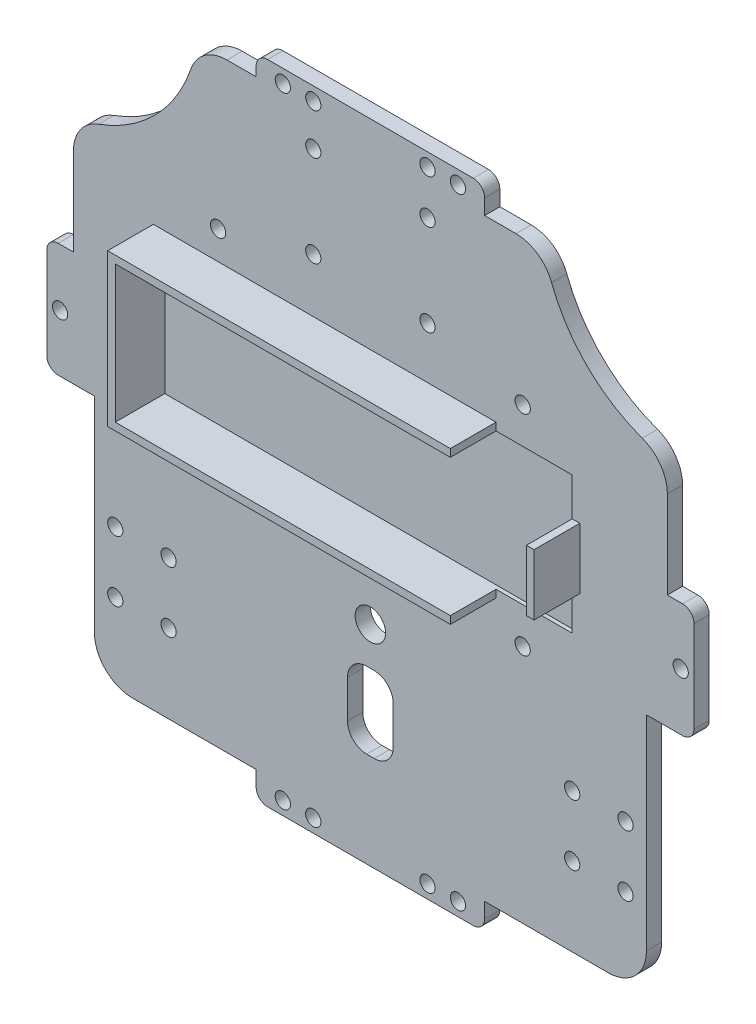
SolidWorks part; units mm, degrees
ref_plane "Front Plane" through (0, 0, 0) normal (0, 0, 1) x (1, 0, 0)
ref_plane "Top Plane" through (0, 0, 0) normal (0, 1, 0) x (1, 0, 0)
ref_plane "Right Plane" through (0, 0, 0) normal (1, 0, 0) x (0, 0, -1)
sketch "Sketch1" plane through (0, 0, 0) normal (0, 0, 1) x (1, 0, 0)
  line L0 (82, 15) -> (78, 15)
  line L7 (78, 15) -> (78, 37.9787)
  line L10 (85, -12) -> (85, 12)
  line L11 (30, -82.6865) -> (30, -78.6865)
  line L12 (-82, 15) -> (-78, 15)
  line L13 (-82, -15) -> (-72.5, -15)
  line L14 (-85, -12) -> (-85, 12)
  line L16 (-78, 15) -> (-78, 37.9787)
  line L17 (72.5, -15) -> (82, -15)
  line L18 (30, 81.3135) -> (30, 77.3135)
  line L19 (30, 77.3135) -> (38.2326, 77.3135)
  line L20 (-30, 81.3135) -> (-30, 78.8612)
  line L21 (-30, 78.8612) -> (-37.6762, 78.8612)
  line L22 (-27, 84.3135) -> (27, 84.3135)
  line L23 (30, -78.6865) -> (62.5, -78.6865)
  line L24 (-30, -82.6865) -> (-30, -78.6865)
  line L25 (-30, -78.6865) -> (-62.5, -78.6865)
  line L26 (-27, -85.6865) -> (27, -85.6865)
  line L27 (72.5, -15) -> (72.5, -68.6865)
  line L28 (-72.5, -68.6865) -> (-72.5, -15)
  arc A0 (47.5861, 70.8508) -> (71.4, 47.383) centre (85, 85) ccw
  arc A1 (-71.4, 47.383) -> (-47.141, 72.0889) centre (-85, 85) ccw
  arc A2 (-27, 84.3135) -> (-30, 81.3135) centre (-27, 81.3135) ccw
  arc A3 (85, 12) -> (82, 15) centre (82, 12) ccw
  arc A4 (30, 81.3135) -> (27, 84.3135) centre (27, 81.3135) ccw
  arc A5 (82, -15) -> (85, -12) centre (82, -12) ccw
  arc A6 (-82, -15) -> (-85, -12) centre (-82, -12) cw
  arc A7 (-85, 12) -> (-82, 15) centre (-82, 12) cw
  arc A8 (-27, -85.6865) -> (-30, -82.6865) centre (-27, -82.6865) cw
  arc A9 (27, -85.6865) -> (30, -82.6865) centre (27, -82.6865) ccw
  arc A10 (-37.6762, 78.8612) -> (-47.141, 72.0889) centre (-37.6762, 68.8612) ccw
  arc A11 (-78, 37.9787) -> (-71.4, 47.383) centre (-68, 37.9787) cw
  arc A12 (47.5861, 70.8508) -> (38.2326, 77.3135) centre (38.2326, 67.3135) ccw
  arc A13 (78, 37.9787) -> (71.4, 47.383) centre (68, 37.9787) ccw
  arc A14 (72.5, -68.6865) -> (62.5, -78.6865) centre (62.5, -68.6865) cw
  arc A15 (-72.5, -68.6865) -> (-62.5, -78.6865) centre (-62.5, -68.6865) ccw
  point P0 (0, 0)
  point P23 (85, 15)
  point P33 (30, 84.3135)
  point P36 (85, -15)
  point P47 (30, -85.6865)
  point P56 (78, 45.6173)
  dimension "D4" = 40
  dimension "D5" = 40
  dimension "D6" = 145
  dimension "D31" = 3
  dimension "D29" = 3
  dimension "D32" = 3
  dimension "D33" = 3
  dimension "D34" = 3
  dimension "D35" = 3
  dimension "D36" = 3
  dimension "D37" = 10
  dimension "D38" = 10
  dimension "D39" = 10
  dimension "D40" = 10
  dimension "D41" = 10
  dimension "D42" = 10
  dimension "D7" = 55
  dimension "D8" = 55
  dimension "D9" = 30
  dimension "D10" = 12.5
  dimension "D11" = 7
  dimension "D12" = 55
  dimension "D13" = 7
  dimension "D14" = 55
  dimension "D15" = 7
  dimension "D16" = 85
  dimension "D17" = 170
  dimension "D18" = 7
  dimension "D19" = 170.6865
  dimension "D20" = 85.6865
  dimension "D21" = 7
  dimension "D22" = 170
  dimension "D23" = 30.6173
  dimension "D24" = 70.6865
  dimension "D25" = 5.4523
  dimension "D26" = 70.6865
  dimension "D27" = 30
  dimension "D28" = 170.6865
  dimension "D30" = 170
extrude "Boss-Extrude1" add sketch "Sketch1" along normal blind 4
sketch "Sketch2" plane through (0, 0, 4) normal (0, 0, 1) x (1, 0, 0)
  line L0 (82, 15) -> (78, 15) construction
  line L1 (85, -12) -> (85, 12) construction
  line L2 (-85, 12) -> (-85, -12) construction
  line L3 (-78, 15) -> (-82, 15) construction
  line L4 (27, 84.3135) -> (-27, 84.3135) construction
  line L5 (30, 77.3135) -> (30, 81.3135) construction
  line L6 (-30, 81.3135) -> (-30, 78.8612) construction
  line L7 (-27, -85.6865) -> (27, -85.6865) construction
  line L8 (30, -82.6865) -> (30, -78.6865) construction
  line L9 (-30, -78.6865) -> (-30, -82.6865) construction
  line L19 (-1, -40.6865) -> (1, -40.6865)
  line L20 (-6, -45.6865) -> (-6, -55.6865)
  line L21 (-1, -60.6865) -> (1, -60.6865)
  line L22 (6, -45.6865) -> (6, -55.6865)
  line L23 (72.5, -15) -> (82, -15) construction
  line L26 (-62.5, -78.6865) -> (-30, -78.6865) construction
  line L27 (-72.5, -15) -> (-72.5, -68.6865) construction
  circle A0 centre (81.5, 0) radius 2
  circle A1 centre (-81.5, 0) radius 2
  circle A2 centre (15, 80.8135) radius 2
  circle A3 centre (23, 80.8135) radius 2
  circle A4 centre (-23, 80.8135) radius 2
  circle A5 centre (-15, 80.8135) radius 2
  circle A6 centre (-23, -82.1865) radius 2
  circle A7 centre (-15, -82.1865) radius 2
  circle A8 centre (15, -82.1865) radius 2
  circle A9 centre (23, -82.1865) radius 2
  circle A11 centre (67, -42) radius 2
  circle A12 centre (67, -58) radius 2
  arc A19 (6, -45.6865) -> (1, -40.6865) centre (1, -45.6865) ccw
  arc A20 (-6, -45.6865) -> (-1, -40.6865) centre (-1, -45.6865) cw
  arc A21 (1, -60.6865) -> (6, -55.6865) centre (1, -55.6865) ccw
  arc A22 (-1, -60.6865) -> (-6, -55.6865) centre (-1, -55.6865) cw
  circle A25 centre (-40, -15.6865) radius 2
  circle A26 centre (40, -15.6865) radius 2
  circle A27 centre (40, 39.3135) radius 2
  circle A28 centre (-40, 39.3135) radius 2
  circle A29 centre (0, -30.6865) radius 4
  circle A30 centre (-15, 70.0079) radius 2
  circle A31 centre (15, 69.3135) radius 2
  circle A32 centre (-15, 46.0079) radius 2
  circle A33 centre (15, 45.3135) radius 2
  circle A34 centre (53, -58) radius 2
  circle A35 centre (53, -42) radius 2
  circle A36 centre (-53, -58) radius 2
  circle A37 centre (-67, -58) radius 2
  circle A38 centre (-67, -42) radius 2
  circle A39 centre (-53, -42) radius 2
  point P59 (6, -40.6865)
  point P65 (-6, -40.6865)
  dimension "D1" = 4
  dimension "D4" = 4
  dimension "D7" = 4
  dimension "D8" = 4
  dimension "D13" = 4
  dimension "D14" = 4
  dimension "D17" = 3.5
  dimension "D21" = 4
  dimension "D22" = 4
  dimension "D25" = 4
  dimension "D26" = 4
  dimension "D31" = 4
  dimension "D32" = 4
  dimension "D33" = 4
  dimension "D34" = 4
  dimension "D43" = 16
  dimension "D44" = 20.6865
  dimension "D45" = 16
  dimension "D46" = 4
  dimension "D59" = 5
  dimension "D60" = 5
  dimension "D61" = 5
  dimension "D62" = 45
  dimension "D63" = 45
  dimension "D68" = 4
  dimension "D69" = 4
  dimension "D70" = 15
  dimension "D71" = 4
  dimension "D66" = 8
  dimension "D80" = 70
  dimension "D35" = 4
  dimension "D37" = 14
  dimension "D38" = 14
  dimension "D42" = 27.6865
  dimension "D47" = 19.5
  dimension "D48" = 14
  dimension "D49" = 4
  dimension "D50" = 14
  dimension "D51" = 16
  dimension "D52" = 20.6865
  dimension "D53" = 19.5
  dimension "D54" = 4
  dimension "D83" = 14.3056
  dimension "D84" = 4
  dimension "D85" = 4
  dimension "D86" = 4
  dimension "D87" = 4
  dimension "D88" = 4
  dimension "D2" = 15
  dimension "D3" = 3.5
  dimension "D5" = 3.5
  dimension "D6" = 15
  dimension "D9" = 3.5
  dimension "D10" = 3.5
  dimension "D11" = 7
  dimension "D12" = 15
  dimension "D15" = 15
  dimension "D16" = 7
  dimension "D18" = 3.5
  dimension "D19" = 3.5
  dimension "D20" = 3.5
  dimension "D23" = 7
  dimension "D24" = 15
  dimension "D27" = 3.5
  dimension "D28" = 3.5
  dimension "D29" = 7
  dimension "D30" = 15
  dimension "D36" = 16
  dimension "D39" = 27
  dimension "D40" = 18
  dimension "D41" = 18
  dimension "D55" = 12
  dimension "D56" = 79
  dimension "D57" = 25
  dimension "D58" = 20
  dimension "D64" = 45
  dimension "D65" = 45
  dimension "D67" = 55
  dimension "D72" = 55
  dimension "D73" = 55
  dimension "D74" = 45
  dimension "D75" = 45
  dimension "D76" = 85
  dimension "D77" = 24
  dimension "D78" = 24
  dimension "D79" = 30
  dimension "D81" = 70
  dimension "D82" = 30
extrude "Cut-Extrude1" cut sketch "Sketch2" against normal blind 5
sketch "Sketch3" plane through (0, 0, 4) normal (0, 0, 1) x (1, 0, 0)
  line L0 (-57, -8.1865) -> (33, -8.1865)
  line L14 (85, -12) -> (85, 12) construction
  line L24 (33, 31.8135) -> (-57, 31.8135)
  line L25 (-57, 31.8135) -> (-57, -8.1865)
  line L26 (27, 84.3135) -> (-27, 84.3135) construction
  line L30 (33, 31.8135) -> (33, 29.8135)
  line L31 (33, 29.8135) -> (53, 29.8135)
  line L32 (53, 29.8135) -> (53, 19.8135)
  line L33 (53, 19.8135) -> (55, 19.8135)
  line L34 (55, 3.8135) -> (53, 3.8135)
  line L35 (53, 3.8135) -> (53, -6.1865)
  line L36 (53, -6.1865) -> (33, -6.1865)
  line L37 (33, -6.1865) -> (33, -8.1865)
  line L38 (55, 19.8135) -> (55, 3.8135)
  dimension "D3" = 112
  dimension "D4" = 16
  dimension "D5" = 28
  dimension "D6" = 2
  dimension "D7" = 52.5
  dimension "D8" = 40
  dimension "D9" = 2
  dimension "D10" = 30
  dimension "D11" = 2
  dimension "D12" = 2
  dimension "D19" = 20
  dimension "D21" = 20
extrude "Boss-Extrude2" add sketch "Sketch3" along normal blind 12
sketch "Sketch5" plane through (0, 0, 16) normal (0, 0, 1) x (1, 0, 0)
  line L0 (-57, -8.1865) -> (33, -8.1865) construction
  line L1 (53, 29.8135) -> (-55, 29.8135)
  line L2 (53, 29.8135) -> (53, -6.1865)
  line L3 (53, -6.1865) -> (-55, -6.1865)
  line L4 (-55, 29.8135) -> (-55, -6.1865)
  line L5 (-57, 31.8135) -> (-57, -8.1865) construction
  dimension "D1" = 2
  dimension "D2" = 2
extrude "Cut-Extrude3" cut sketch "Sketch5" against normal blind 13
